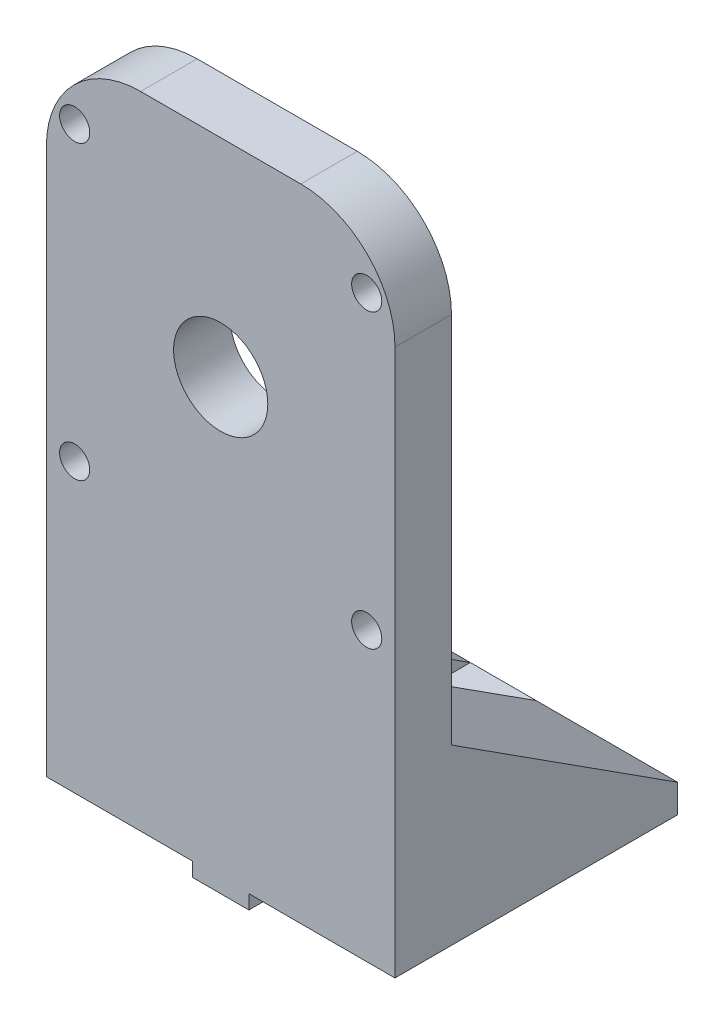
SolidWorks part; units mm, degrees
ref_plane "Спереди" through (0, 0, 0) normal (0, 0, 1) x (1, 0, 0)
ref_plane "Сверху" through (0, 0, 0) normal (0, 1, 0) x (1, 0, 0)
ref_plane "Справа" through (0, 0, 0) normal (1, 0, 0) x (0, 0, -1)
other "Configuration Table"
sketch "Эскиз1" plane through (0, 0, 0) normal (0, 0, 1) x (1, 0, 0)
  line L0 (18.5, 65) -> (18.5, 20) construction
  line L2 (0, 0) -> (0, 65)
  line L3 (0, 65) -> (16, 65)
  line L4 (37, 0) -> (37, 65)
  line L5 (0, 0) -> (37, 0)
  line L17 (16, 65) -> (21, 65)
  line L33 (21, 65) -> (37, 65)
  circle A1 centre (18.5, 43) radius 5
  point P9 (17.5066, 55)
  dimension "D2" = 18.5
  dimension "D3" = 10
  dimension "D1" = 37
  dimension "D9" = 65
extrude "Бобышка-Вытянуть1" add sketch "Эскиз1" along normal blind 6
fillet "Скругление1" radius 10 2 edges at (37, 65, 3) (0, 65, 3)
sketch "Эскиз4" plane through (0, 0, 6) normal (0, 0, 1) x (1, 0, 0)
  line L0 (0, 0) -> (37, 0) construction
  line L1 (37, 0) -> (0, 0)
  line L2 (37, 0) -> (37, -3)
  line L3 (37, -3) -> (0, -3)
  line L4 (0, 0) -> (0, -3)
  line L7 (0, 55) -> (0, 0) construction
  line L8 (37, 0) -> (37, 55) construction
  dimension "D1" = 3
  dimension "D2" = 0
  dimension "D3" = 0
extrude "Бобышка-Вытянуть2" add sketch "Эскиз4" against normal blind 30
sketch "Эскиз5" plane through (0, 0, 6) normal (0, 0, 1) x (1, 0, 0)
  line L0 (0, -3) -> (37, -3) construction
  line L1 (21.5, -3) -> (15.5, -3)
  line L2 (21.5, -3) -> (21.5, -4.5)
  line L3 (21.5, -4.5) -> (15.5, -4.5)
  line L4 (15.5, -3) -> (15.5, -4.5)
  line L6 (18.5, -3) -> (18.5, -12.5673) construction
  line L7 (0, -3) -> (37, -3) construction
  dimension "D1" = 3
  dimension "D2" = 6
  dimension "D3" = 1.5
extrude "Бобышка-Вытянуть3" add sketch "Эскиз5" against normal up to surface (30 mm away) up to face at (18.5, -1.5, -24)
sketch "Эскиз6" plane through (0, 0, 6) normal (0, 0, 1) x (1, 0, 0)
  line L0 (0, 55) -> (0, -3) construction
  line L1 (13.5, 43) -> (23.5, 43) construction
  line L3 (18.5, 48) -> (18.5, 38) construction
  circle A0 centre (3, 27.5) radius 1.6
  circle A1 centre (18.5, 43) radius 5 construction
  circle A2 centre (3, 58.5) radius 1.6
  circle A3 centre (34, 27.5) radius 1.6
  circle A4 centre (34, 58.5) radius 1.6
  dimension "D1" = 3
  dimension "D3" = 3.2
  dimension "D2" = 15.5
extrude "Вырез-Вытянуть1" cut sketch "Эскиз6" against normal blind 10 contours A0 | A3 | A4 | A2
sketch "Эскиз9" plane through (0, 0, 0) normal (-1, 0, 0) x (0, 0, 1)
  line L0 (0, 55) -> (0, 0) construction
  line L1 (-24, 0) -> (0, 0)
  line L4 (0, 0) -> (0, 15.4162)
  line L5 (-24, 0) -> (0, 15.4162)
extrude "Бобышка-Вытянуть5" add sketch "Эскиз9" against normal blind 15
sketch "Эскиз10" plane through (0, -4.5, 0) normal (0, -1, 0) x (1, 0, 0)
  line L0 (18.5, 6) -> (18.5, -24) construction
  line L1 (15.5, 6) -> (21.5, 6) construction
  line L2 (15.5, -24) -> (21.5, -24) construction
  line L3 (15.5, -4) -> (21.3516, -4) construction
  line L6 (15.5, -24) -> (15.5, 6) construction
  line L7 (15.5, -9) -> (21.5, -9) construction
  line L8 (15.5, -24) -> (15.5, 6) construction
  line L9 (21.5, -24) -> (21.5, 6) construction
  line L11 (21.5, -18) -> (15.5, -18) construction
  circle A1 centre (18.5, -18) radius 1.75
  circle A2 centre (18.4258, -4) radius 1.75
  dimension "D1" = 15
  dimension "D4" = 3.5
  dimension "D5" = 3.5
  dimension "D3" = 14
  dimension "D2" = 10
extrude "Вырез-Вытянуть3" cut sketch "Эскиз10" against normal blind 1000
sketch "Эскиз11" plane through (37, 0, 0) normal (1, 0, 0) x (0, 0, -1)
  line L1 (0, 0) -> (24, 0)
  line L2 (0, 0) -> (0, 15.4162)
  line L5 (0, 15.4162) -> (24, 0)
  line L6 (24, -3) -> (24, 0) construction
  dimension "D1" = 0
extrude "Бобышка-Вытянуть6" add sketch "Эскиз11" against normal blind 15
